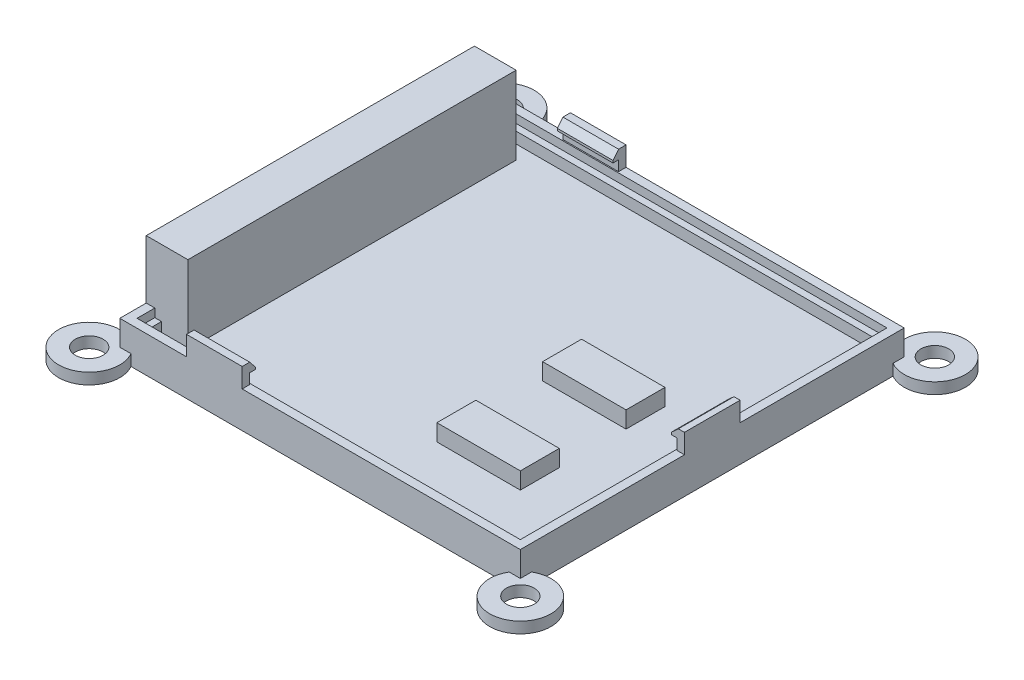
SolidWorks part; units mm, degrees
material "ABS"
ref_plane "Front Plane" through (0, 0, 0) normal (0, 0, 1) x (1, 0, 0)
ref_plane "Top Plane" through (0, 0, 0) normal (0, 1, 0) x (1, 0, 0)
ref_plane "Right Plane" through (0, 0, 0) normal (1, 0, 0) x (0, 0, -1)
sketch "Sketch2" plane through (0, 0, 0) normal (0, 1, 0) x (1, 0, 0)
  line L1 (-33.25, 31.75) -> (33.25, 31.75)
  line L2 (-33.25, 31.75) -> (-33.25, -31.75)
  line L3 (-33.25, -31.75) -> (33.25, -31.75)
  line L4 (33.25, 31.75) -> (33.25, -31.75)
  line L5 (-33.25, 31.75) -> (33.25, -31.75) construction
  line L6 (-33.25, -31.75) -> (33.25, 31.75) construction
  point P0 (0, 0)
  dimension "D1" = 66.5
  dimension "D2" = 63.5
extrude "Boss-Extrude1" add sketch "Sketch2" along normal blind 3
sketch "Sketch6" plane through (0, 0, 0) normal (0, 1, 0) x (1, 0, 0)
  line L1 (-33.25, 31.75) -> (33.25, 31.75)
  line L2 (-33.25, 31.75) -> (-33.25, -31.75)
  line L3 (-33.25, -31.75) -> (33.25, -31.75)
  line L4 (33.25, 31.75) -> (33.25, -31.75)
  line L5 (-33.25, 31.75) -> (33.25, -31.75) construction
  line L6 (-33.25, -31.75) -> (33.25, 31.75) construction
  line L7 (-36, 34.5) -> (36, 34.5)
  line L8 (-36, 34.5) -> (-36, -34.5)
  line L9 (-36, -34.5) -> (36, -34.5)
  line L10 (36, 34.5) -> (36, -34.5)
  line L11 (-36, 34.5) -> (36, -34.5) construction
  line L12 (-36, -34.5) -> (36, 34.5) construction
  point P0 (0, 0)
  point P7 (0, 0)
  dimension "D1" = 2.75
  dimension "D2" = 2.75
extrude "Boss-Extrude2" add sketch "Sketch6" along normal blind 5
sketch "Sketch14" plane through (0, 3, 0) normal (0, 1, 0) x (1, 0, 0)
  line L1 (-28.5, 29.25) -> (-36, 29.25)
  line L2 (-28.5, 29.25) -> (-28.5, -29.75)
  line L3 (-28.5, -29.75) -> (-36, -29.75)
  line L4 (-36, 29.25) -> (-36, -29.75)
  line L5 (-36, 34.5) -> (-36, -34.5) construction
  line L6 (36, 34.5) -> (-36, 34.5) construction
  line L7 (-36, -34.5) -> (36, -34.5) construction
  dimension "D1" = 5.25
  dimension "D2" = 4.75
  dimension "D3" = 7.5
extrude "Boss-Extrude4" add sketch "Sketch14" along normal blind 14
sketch "Sketch15" plane through (0, 5, 0) normal (0, 1, 0) x (1, 0, 0)
  line L0 (-34.45, 32.95) -> (34.45, 32.95)
  line L1 (-36, 34.5) -> (36, 34.5)
  line L2 (-36, 34.5) -> (-36, 29.25)
  line L3 (-36, -34.5) -> (36, -34.5)
  line L4 (36, 34.5) -> (36, -34.5)
  line L5 (-36, 34.5) -> (36, -34.5) construction
  line L6 (-36, -34.5) -> (36, 34.5) construction
  line L7 (34.45, 32.95) -> (34.45, -32.95)
  line L8 (-34.45, -32.95) -> (34.45, -32.95)
  line L9 (-34.45, 32.95) -> (-34.45, 29.25)
  line L10 (-36, -29.75) -> (-34.45, -29.75)
  line L11 (-36, -29.75) -> (-33.25, -29.75) construction
  line L12 (-36, 29.25) -> (-34.45, 29.25)
  line L13 (-36, -29.75) -> (-36, -34.5)
  line L14 (-36, 34.5) -> (-36, -34.5) construction
  line L15 (-34.45, -29.75) -> (-34.45, -32.95)
  line L16 (-34.45, 32.95) -> (-34.45, -32.95) construction
  point P0 (0, 0)
  dimension "D1" = 1.55
extrude "Boss-Extrude5" add sketch "Sketch15" along normal blind 1.5
sketch "Sketch16" plane through (0, 0, 0) normal (0, -1, 0) x (1, 0, 0)
  line L0 (-38.75, -37.25) -> (-38.75, 37.25) construction
  line L1 (-36, -34.5) -> (36, -34.5) construction
  line L2 (-36, -34.5) -> (-36, 34.5) construction
  line L3 (-36, 34.5) -> (36, 34.5) construction
  line L4 (36, -34.5) -> (36, 34.5) construction
  line L5 (-36, -34.5) -> (36, 34.5) construction
  line L6 (-36, 34.5) -> (36, -34.5) construction
  line L7 (-38.75, 37.25) -> (38.75, 37.25) construction
  line L8 (38.75, -37.25) -> (38.75, 37.25) construction
  line L9 (-38.75, -37.25) -> (38.75, -37.25) construction
  circle A0 centre (38.75, 37.25) radius 2.5
  circle A1 centre (-38.75, 37.25) radius 2.5
  circle A2 centre (-38.75, -37.25) radius 2.5
  circle A3 centre (38.75, -37.25) radius 2.5
  circle A4 centre (-38.75, 37.25) radius 5.5
  circle A5 centre (38.75, 37.25) radius 5.5
  circle A6 centre (38.75, -37.25) radius 5.5
  circle A7 centre (-38.75, -37.25) radius 5.5
  point P0 (0, 0)
  dimension "D2" = 5
  dimension "D3" = 5
  dimension "D4" = 5
  dimension "D5" = 5
  dimension "D1" = 2.75
  dimension "D6" = 3
extrude "Boss-Extrude6" add sketch "Sketch16" against normal blind 2
ref_plane "Plane2" through (-24, 0, 0) normal (-1, 0, 0) x (0, 0, 1)
sketch "Sketch17" plane through (-24, 0, 0) normal (-1, 0, 0) x (0, 0, 1)
  line L0 (-1002.257, 9.5) -> (48997.743, 9.5) construction
  line L1 (-32.4869, 0) -> (32.4869, 0) construction
  line L2 (34.5, -995.6937) -> (34.5, 49004.3063) construction
  line L3 (32.95, -995.6892) -> (32.95, 49004.3108) construction
  line L4 (34.5, 6.5) -> (33.15, 6.5)
  line L5 (33.15, 6.5) -> (33.15, 8.35)
  line L6 (33.15, 8.35) -> (32.15, 8.35)
  line L7 (32.15, 8.35) -> (32.15, 8.75)
  line L8 (32.15, 8.75) -> (33.15, 10)
  line L9 (33.15, 10) -> (34.5, 10)
  line L10 (34.5, 10) -> (34.5, 6.5)
  dimension "D1" = 9.5
  dimension "D2" = 34.5
  dimension "D3" = 1.55
  dimension "D4" = 1.35
  dimension "D5" = 3.5
  dimension "D6" = 0.4
  dimension "D7" = 1
  dimension "D8" = 1.85
extrude "Boss-Extrude7" add sketch "Sketch17" against normal blind 10
mirror "Mirror1" about plane through (0, 0, 0) normal (0, 0, 1) of "Boss-Extrude7"
sketch "Sketch18" plane through (0, 0, 0) normal (0, 0, 1) x (1, 0, 0)
  line L0 (36, -990.3462) -> (36, 49009.6538) construction
  line L1 (-964.8642, 6.5) -> (49035.1358, 6.5) construction
  line L2 (36, 6.5) -> (34.65, 6.5)
  line L3 (34.65, 6.5) -> (34.65, 8.45)
  line L4 (34.65, 8.45) -> (33.65, 8.45)
  line L5 (33.65, 8.45) -> (33.65, 8.85)
  line L6 (33.65, 8.85) -> (34.9002, 10)
  line L7 (34.9002, 10) -> (36, 10)
  line L8 (36, 10) -> (36, 6.5)
  dimension "D1" = 36
  dimension "D2" = 6.5
  dimension "D3" = 3.5
  dimension "D4" = 1.95
  dimension "D5" = 0.4
  dimension "D6" = 1.35
  dimension "D7" = 1
extrude "Boss-Extrude8" add sketch "Sketch18" along normal mid plane 10 contours L6 L7 L8 L2 L3 L4 L5
sketch "Sketch19" plane through (0, 3, 0) normal (0, 1, 0) x (1, 0, 0)
  line L0 (-33.25, -31.75) -> (33.25, -31.75) construction
  line L1 (8.25, -14.75) -> (23.25, -14.75)
  line L2 (8.25, -14.75) -> (8.25, -21.75)
  line L3 (8.25, -21.75) -> (23.25, -21.75)
  line L4 (23.25, -14.75) -> (23.25, -21.75)
  line L5 (33.25, -31.75) -> (33.25, 31.75) construction
  line L6 (-984.591, -8.75) -> (49015.409, -8.75) construction
  line L7 (8.25, 4.25) -> (23.25, 4.25)
  line L8 (23.25, -2.75) -> (23.25, 4.25)
  line L9 (8.25, -2.75) -> (23.25, -2.75)
  line L10 (8.25, -2.75) -> (8.25, 4.25)
  dimension "D1" = 7
  dimension "D2" = 15
  dimension "D3" = 10
  dimension "D4" = 10
  dimension "D5" = 6
extrude "Boss-Extrude9" add sketch "Sketch19" along normal blind 3
